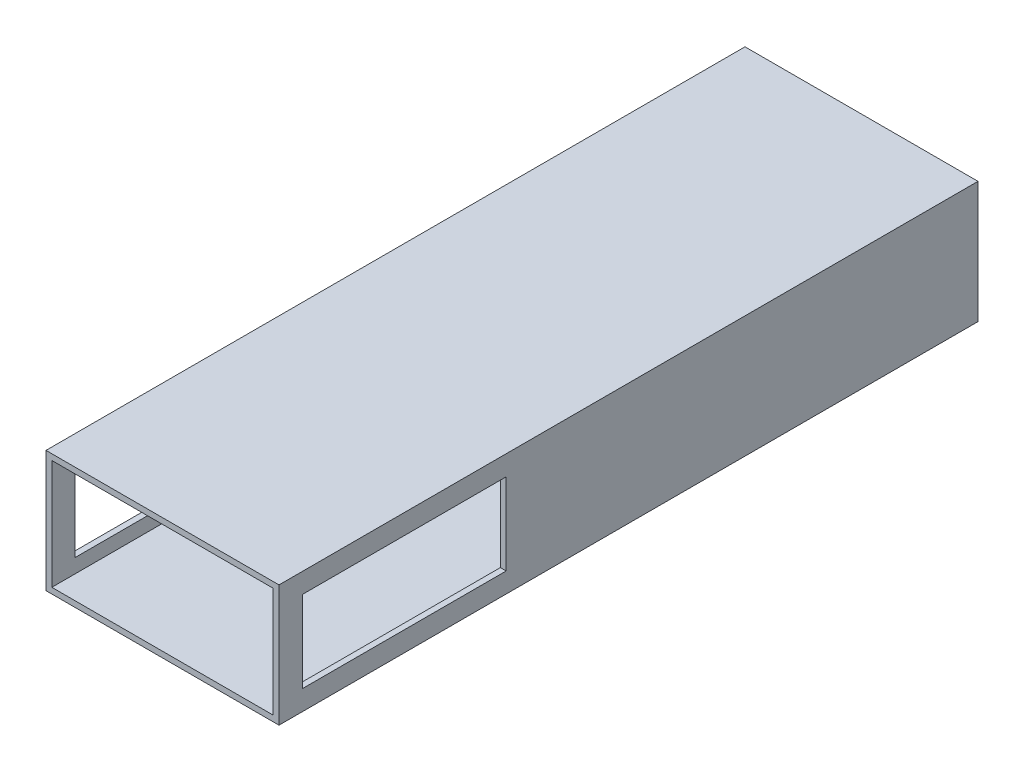
SolidWorks part; units mm, degrees
ref_plane "Alzado" through (0, 0, 0) normal (0, 0, 1) x (1, 0, 0)
ref_plane "Planta" through (0, 0, 0) normal (0, 1, 0) x (1, 0, 0)
ref_plane "Vista lateral" through (0, 0, 0) normal (1, 0, 0) x (0, 0, -1)
sketch "Croquis1" plane through (0, 0, 0) normal (0, 0, 1) x (1, 0, 0)
  line L0 (19, 9.43) -> (-19, 9.43)
  line L1 (20, -10.43) -> (-20, -10.43)
  line L2 (20, -10.43) -> (20, 10.43)
  line L3 (20, 10.43) -> (-20, 10.43)
  line L4 (-20, -10.43) -> (-20, 10.43)
  line L5 (20, -10.43) -> (-20, 10.43) construction
  line L6 (20, 10.43) -> (-20, -10.43) construction
  line L7 (-19, -9.43) -> (-19, 9.43)
  line L8 (19, -9.43) -> (-19, -9.43)
  line L9 (19, -9.43) -> (19, 9.43)
  point P0 (0, 0)
  dimension "D1" = 40
  dimension "D2" = 20.86
  dimension "D3" = 1
extrude "Saliente-Extruir1" add sketch "Croquis1" along normal blind 120
sketch "Croquis2" plane through (-20, 0, 0) normal (-1, 0, 0) x (0, 0, 1)
  line L0 (120, 0) -> (0, 0) construction
  line L1 (120, 10.43) -> (120, -10.43) construction
  line L3 (81, -7) -> (116, -7)
  line L4 (81, -7) -> (81, 7)
  line L5 (81, 7) -> (116, 7)
  line L6 (116, -7) -> (116, 7)
  line L7 (81, -7) -> (116, 7) construction
  line L8 (81, 7) -> (116, -7) construction
  point P5 (98.5, 0)
  dimension "D1" = 4
  dimension "D2" = 35
  dimension "D3" = 14
extrude "Cortar-Extruir1" cut sketch "Croquis2" against normal blind 120
sketch "Croquis3" plane through (-20, 0, 0) normal (-1, 0, 0) x (0, 0, 1)
  line L0 (110, -10.43) -> (110, 10.43) construction
  line L1 (120, -10.43) -> (0, -10.43) construction
  line L2 (120, 10.43) -> (0, 10.43) construction
  line L3 (120, 10.43) -> (120, -10.43) construction
  line L4 (81, -7) -> (116, -7) construction
  circle A0 centre (110, -2) radius 2.5
  dimension "D2" = 5
  dimension "D3" = 5
  dimension "D1" = 10
